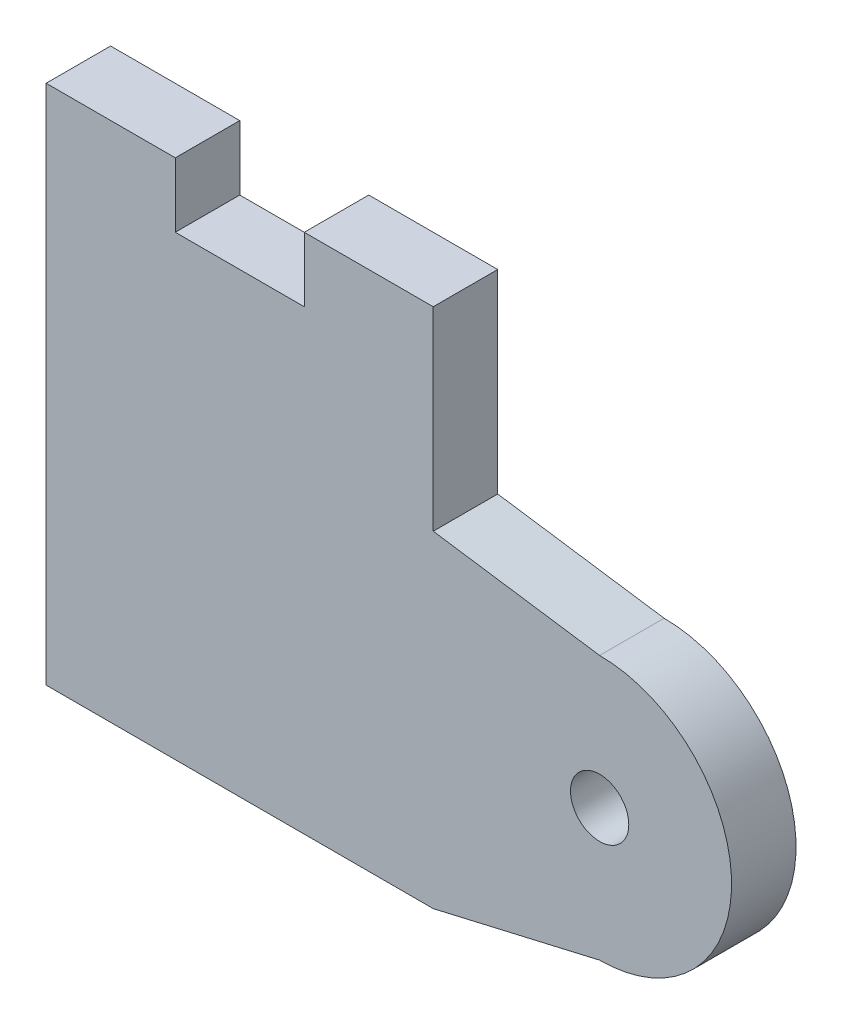
SolidWorks part; units mm, degrees
ref_plane "Front Plane" through (0, 0, 0) normal (0, 0, 1) x (1, 0, 0)
ref_plane "Top Plane" through (0, 0, 0) normal (0, 1, 0) x (1, 0, 0)
ref_plane "Right Plane" through (0, 0, 0) normal (1, 0, 0) x (0, 0, -1)
sketch "Sketch1" plane through (0, 0, 0) normal (0, 0, 1) x (1, 0, 0)
  line L1 (126.6499, 0) -> (113.9499, 0)
  line L2 (126.6499, 0) -> (126.6499, -6.35)
  line L3 (126.6499, -19.1452) -> (157.1679, -19.1452)
  line L4 (113.9499, 0) -> (113.9499, -6.35)
  line L5 (88.5302, 0) -> (101.2499, 0)
  line L6 (88.5302, 0) -> (88.5302, -6.35)
  line L7 (88.5302, -19.1452) -> (88.5302, -51.3292)
  line L8 (101.2499, 0) -> (101.2499, -6.35)
  line L9 (101.2499, -6.35) -> (113.9499, -6.35)
  line L10 (88.5302, -6.35) -> (88.5302, -19.1452)
  line L12 (126.6499, -6.35) -> (126.6499, -19.1452)
  line L13 (88.5302, -51.3292) -> (157.1679, -51.3292)
  line L14 (157.1679, -19.1452) -> (157.1679, -51.3292)
  circle A0 centre (143.0356, -34.5397) radius 2.8702
extrude "Boss-Extrude1" add sketch "Sketch1" along normal blind 6.35
sketch "Sketch2" plane through (0, 0, 6.35) normal (0, 0, 1) x (1, 0, 0)
  line L0 (143.0356, -21.547) -> (126.6499, -19.1452)
  line L1 (143.0356, -47.5324) -> (126.6499, -51.3292)
  line L2 (88.5302, -51.3292) -> (157.1679, -51.3292) construction
  line L3 (126.6499, -51.3292) -> (157.1679, -51.3292)
  line L4 (157.1679, -51.3292) -> (157.1679, -19.1452)
  line L5 (157.1679, -19.1452) -> (126.6499, -19.1452)
  arc A0 (143.0356, -47.5324) -> (143.0356, -21.547) centre (143.0356, -34.5397) ccw
extrude "Cut-Extrude1" cut sketch "Sketch2" against normal through all
